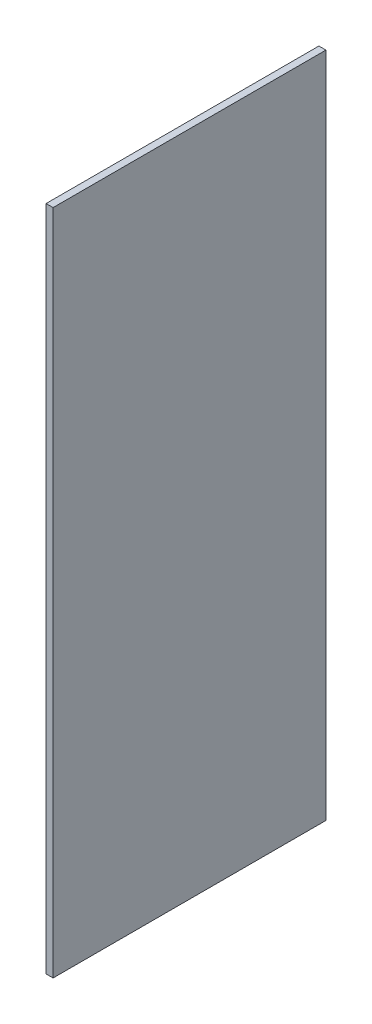
SolidWorks part; units mm, degrees
ref_plane "Спереди" through (0, 0, 0) normal (0, 0, 1) x (1, 0, 0)
ref_plane "Сверху" through (0, 0, 0) normal (0, 1, 0) x (1, 0, 0)
ref_plane "Справа" through (0, 0, 0) normal (1, 0, 0) x (0, 0, -1)
ref_plane "Плоскость4" through (0.5, 0, 0) normal (-1, 0, 0) x (0, -1, 0)
sketch "Эскиз1" plane through (0.5, 0, 0) normal (-1, 0, 0) x (0, -1, 0)
  line L0 (-5.85, 42.25) -> (-100.85, 42.25)
  line L1 (-100.85, 42.25) -> (-100.85, 3.4)
  line L2 (-100.85, 3.4) -> (-5.85, 3.4)
  line L3 (-5.85, 3.4) -> (-5.85, 42.25)
extrude "Бобышка-Вытянуть1" add sketch "Эскиз1" against normal blind 1
sketch "Эскиз2" plane through (0.5, 0, 0) normal (-1, 0, 0) x (0, 0, 1)
  line L0 (39.55, 8.55) -> (6.1, 8.55)
  line L1 (6.1, 8.55) -> (6.1, 98.15)
  line L2 (6.1, 98.15) -> (39.55, 98.15)
  line L3 (39.55, 98.15) -> (39.55, 8.55)
extrude "Бобышка-Вытянуть2" add sketch "Эскиз2" along normal blind 0.5
